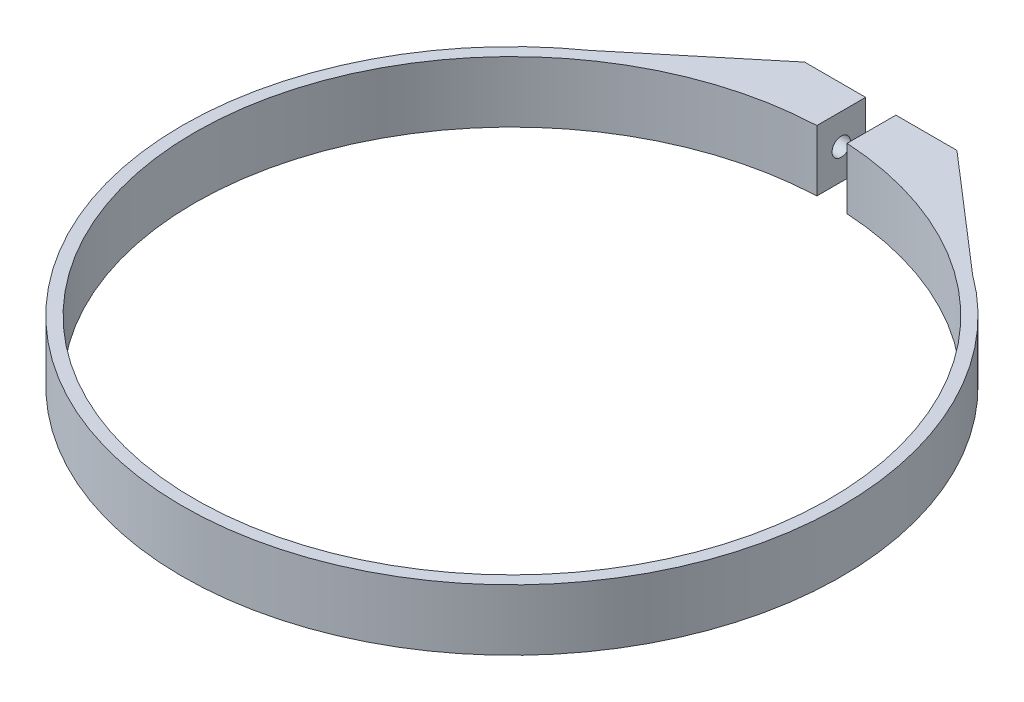
SolidWorks part; units mm, degrees
ref_plane "Front Plane" through (0, 0, 0) normal (0, 0, 1) x (1, 0, 0)
ref_plane "Top Plane" through (0, 0, 0) normal (0, 1, 0) x (1, 0, 0)
ref_plane "Right Plane" through (0, 0, 0) normal (1, 0, 0) x (0, 0, -1)
ref_plane "Plane1" through (0, 10, 0) normal (0, 1, 0) x (1, 0, 0)
sketch "Sketch1" plane through (0, 10, 0) normal (0, 1, 0) x (1, 0, 0)
  line L0 (2.9897, 59.914) -> (2.9897, 51.914)
  line L1 (-2.0103, 51.9611) -> (-2.0103, 59.9611)
  line L2 (-2.0103, 59.9611) -> (-12.0103, 59.9611)
  line L3 (-12.0103, 59.9611) -> (-31.2716, 44.0237)
  line L4 (31.9047, 43.567) -> (12.9897, 59.914)
  line L5 (12.9897, 59.914) -> (2.9897, 59.914)
  arc A0 (2.9897, 51.914) -> (-2.0103, 51.9611) centre (0, 0) ccw
  arc A1 (-31.2716, 44.0237) -> (31.9047, 43.567) centre (0, 0) ccw
extrude "Boss-Extrude1" add sketch "Sketch1" against normal blind 10
sketch "Sketch2" plane through (0, 0, 0) normal (0, 0, 1) x (1, 0, 0)
  line L0 (52, 10) -> (0, 10)
  line L1 (0, 10) -> (0, 0)
  line L2 (0, 0) -> (52, 0)
  line L3 (52, 0) -> (52, 10)
  line L4 (0, 10) -> (0, 0) construction
revolve "Cut-Revolve1" cut sketch "Sketch2" angle 360 about L4
hole_wizard "Ø2.5 (2.5) Diameter Hole1" positions "Sketch4" profile "Sketch3" hole size "Ø2.5" standard "ANSI Metric"
sketch "Sketch4" plane through (2.9897, 0, 0) normal (-1, 0, 0) x (0, 0, 1)
  point P0 (-55.914, 5)
sketch "Sketch3" plane through (2.9897, 5, -55.914) normal (0, 1, 0) x (0, 0, 1)
  line L0 (0, 0) -> (0, 51.0103)
  line L1 (0, 51.0103) -> (1.25, 51.0103)
  line L2 (1.25, 51.0103) -> (1.25, 0)
  line L5 (1.25, 0) -> (0, 0)
  line L11 (0, -6.35) -> (0, 107.95) construction
  dimension "Thru Hole Dia." = 2.5
  dimension "Thru Hole Depth" = 51.0103
ref_plane "Plane2" through (-19.8659, 0, 0) normal (-1, 0, 0) x (0, 0, 1)
hole_wizard "CBORE for M2.5 Hex Head Machine Screw1" positions "Sketch6" profile "Sketch5" counterbore size "M2.5" standard "ANSI Metric"
sketch "Sketch6" plane through (-19.8659, 0, 0) normal (-1, 0, 0) x (0, 0, 1)
  point P0 (-55.9611, 5)
sketch "Sketch5" plane through (-19.8659, 5, -55.9611) normal (0, 1, 0) x (0, 0, 1)
  line L0 (0, 0) -> (0, 73.8659)
  line L1 (0, 73.8659) -> (1.5, 73.8659)
  line L3 (1.5, 73.8659) -> (1.5, 12.8556)
  line L4 (1.5, 12.8556) -> (2.5, 12.8556)
  line L5 (2.5, 12.8556) -> (2.5, 0)
  line L7 (2.5, 0) -> (0, 0)
  line L11 (0, -6.35) -> (0, 107.95) construction
  dimension "Thru Hole Dia." = 3
  dimension "Thru Hole Depth" = 73.8659
  dimension "C'Bore Dia." = 5
  dimension "C'Bore Depth" = 12.8556
